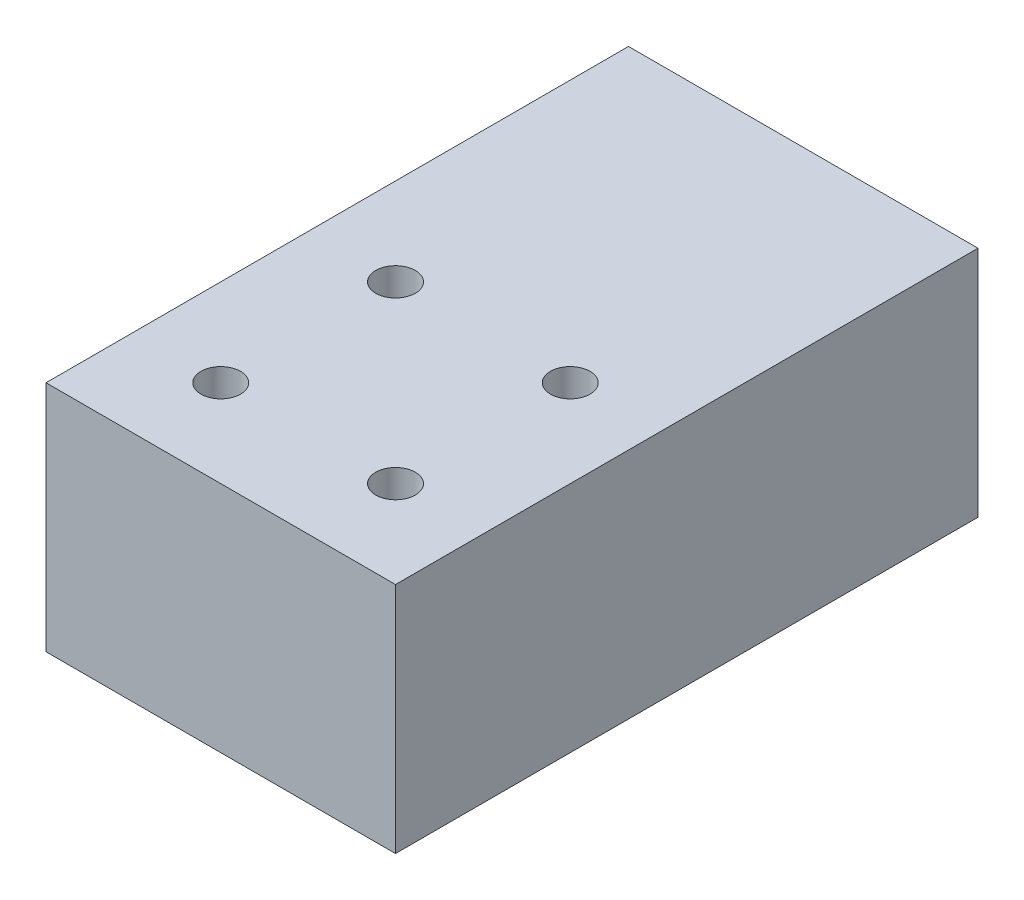
SolidWorks part; units mm, degrees
ref_plane "Front Plane" through (0, 0, 0) normal (0, 0, 1) x (1, 0, 0)
ref_plane "Top Plane" through (0, 0, 0) normal (0, 1, 0) x (1, 0, 0)
ref_plane "Right Plane" through (0, 0, 0) normal (1, 0, 0) x (0, 0, -1)
sketch "Sketch2" plane through (0, 0, 0) normal (0, 0, 1) x (1, 0, 0)
  line L1 (0, 0) -> (30, 0)
  line L2 (0, 0) -> (0, 20)
  line L3 (0, 20) -> (30, 20)
  line L4 (30, 0) -> (30, 20)
  dimension "D1" = 20
  dimension "D2" = 30
extrude "Boss-Extrude1" add sketch "Sketch2" along normal blind 50
sketch "Sketch3" plane through (0, 20, 0) normal (0, 1, 0) x (1, 0, 0)
  line L0 (30, -50) -> (30, 0) construction
  line L1 (0, 0) -> (30, 0) construction
  line L2 (0, 0) -> (0, -20) construction
  line L3 (0, -20) -> (30, -20) construction
  line L4 (30, 0) -> (30, -20) construction
  line L5 (15, -20) -> (15, -50) construction
  line L6 (30, -50) -> (0, -50) construction
  line L7 (15, -35) -> (0, -35) construction
  line L8 (0, -50) -> (0, 0) construction
  line L9 (15, -35) -> (30, -35) construction
  line L10 (22.5, -35) -> (22.5, -50) construction
  line L11 (22.5, -42.5) -> (7.5, -42.5) construction
  line L12 (7.5, -35) -> (7.5, -42.5) construction
  line L13 (7.5, -35) -> (7.5, -20) construction
  line L14 (22.5, -35) -> (22.5, -20) construction
  line L15 (22.5, -27.5) -> (7.5, -27.5) construction
  circle A0 centre (7.5, -27.5) radius 1.7
  circle A1 centre (22.5, -27.5) radius 1.7
  circle A2 centre (22.5, -42.5) radius 1.7
  circle A3 centre (7.5, -42.5) radius 1.7
  point P28 (22.5, -27.7304)
  point P30 (22.7244, -42.5)
  point P32 (7.7664, -42.5)
  dimension "D2" = 3.4
  dimension "D1" = 20
extrude "Cut-Extrude1" cut sketch "Sketch3" against normal blind 50
